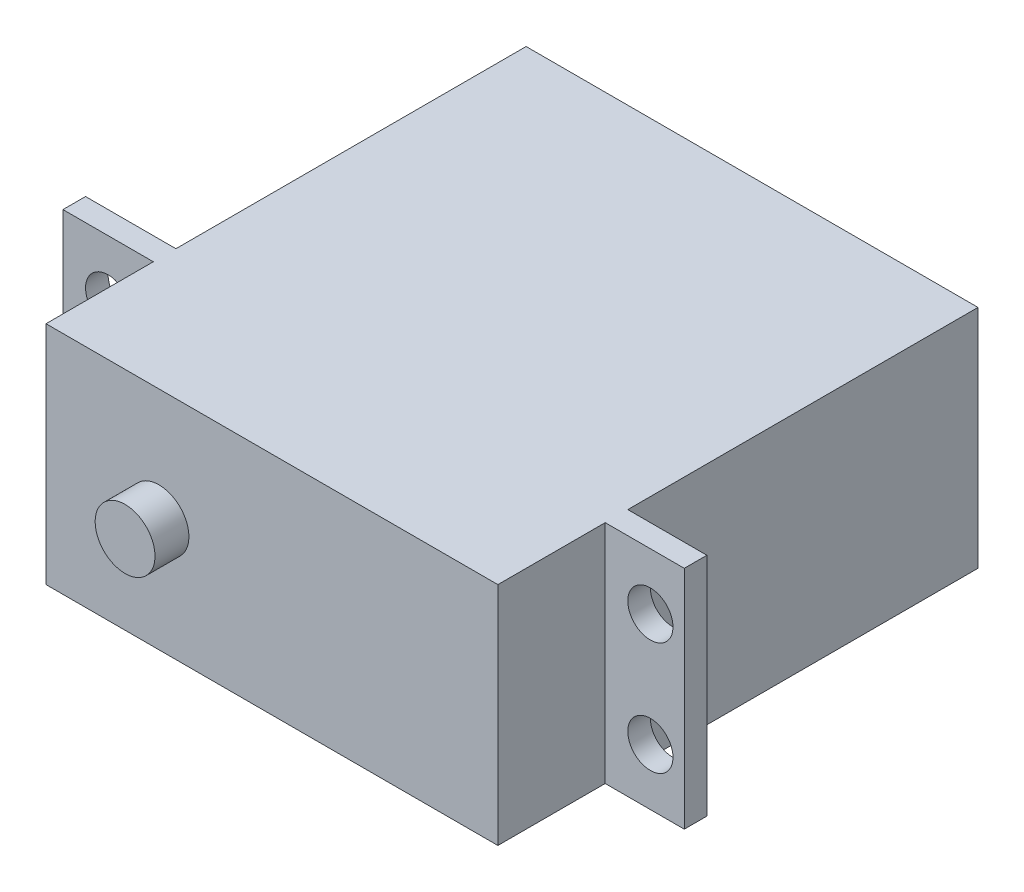
SolidWorks part; units mm, degrees
other "Marquage1"
sketch "Esquisse6" plane through (-18, 10, 3) normal (-0.3855, 0.5343, 0.7523) x (0.7595, -0.2792, 0.5875)
sketch "Esquisse7" plane through (-18, 10, 3) normal (-0.3855, 0.5343, 0.7523) x (0.7595, -0.2792, 0.5875)
ref_plane "Plan de face" through (0, 0, 0) normal (0, 0, 1) x (1, 0, 0)
ref_plane "Plan de dessus" through (0, 0, 0) normal (0, 1, 0) x (1, 0, 0)
ref_plane "Plan de droite" through (0, 0, 0) normal (1, 0, 0) x (0, 0, -1)
sketch "Esquisse1" plane through (0, 0, 0) normal (0, 0, 1) x (1, 0, 0)
  line L1 (-10, -10) -> (30, -10)
  line L2 (-10, -10) -> (-10, 10)
  line L3 (-10, 10) -> (30, 10)
  line L4 (30, -10) -> (30, 10)
  point P5 (-10, 0)
  dimension "D1" = 20
  dimension "D2" = 40
  dimension "D3" = 10
extrude "Boss.-Extru.1" add sketch "Esquisse1" against normal blind 42.5
sketch "Esquisse2" plane through (30, 0, 0) normal (1, 0, 0) x (0, 0, -1)
  line L0 (42.5, 10) -> (0, 10) construction
  line L1 (11.5, 10) -> (9.5, 10)
  line L2 (11.5, 10) -> (11.5, -10)
  line L3 (11.5, -10) -> (9.5, -10)
  line L4 (9.5, 10) -> (9.5, -10)
  line L5 (42.5, -10) -> (0, -10) construction
  line L7 (42.5, -10) -> (42.5, 10) construction
  dimension "D1" = 2
  dimension "D2" = 31
extrude "Boss.-Extru.2" add sketch "Esquisse2" along normal blind 7 and the other way blind 48
sketch "Esquisse3" plane through (0, 0, -11.5) normal (0, 0, -1) x (-1, 0, 0)
  line L0 (-30, 0) -> (10, 0) construction
  line L3 (-10, 0) -> (-10, 10) construction
  line L5 (-30, -10) -> (-30, 10) construction
  line L6 (10, 10) -> (10, -10) construction
  line L7 (-30, 10) -> (10, 10) construction
  circle A0 centre (14, 5) radius 2
  circle A1 centre (14, -5) radius 2
  circle A2 centre (-34, -5) radius 2
  circle A3 centre (-34, 5) radius 2
  point P9 (-10, 0)
  dimension "D1" = 24
  dimension "D3" = 5
extrude "Enlèv. mat.-Extru.1" cut sketch "Esquisse3" against normal blind 7.5
sketch "Esquisse5" plane through (0, 0, 0) normal (0, 0, -1) x (-1, 0, 0)
  circle A0 centre (0, 0) radius 2.65
  dimension "D2" = 5.3
extrude "Boss.-Extru.3" add sketch "Esquisse5" against normal blind 3
sketch "Esquisse8" plane through (0, 0, 0) normal (0, 1, 0) x (1, 0, 0)
  line L0 (0, 0) -> (0, -3) construction
  line L1 (-2.65, -3) -> (2.65, -3) construction
  point P5 (0, -1.5)
